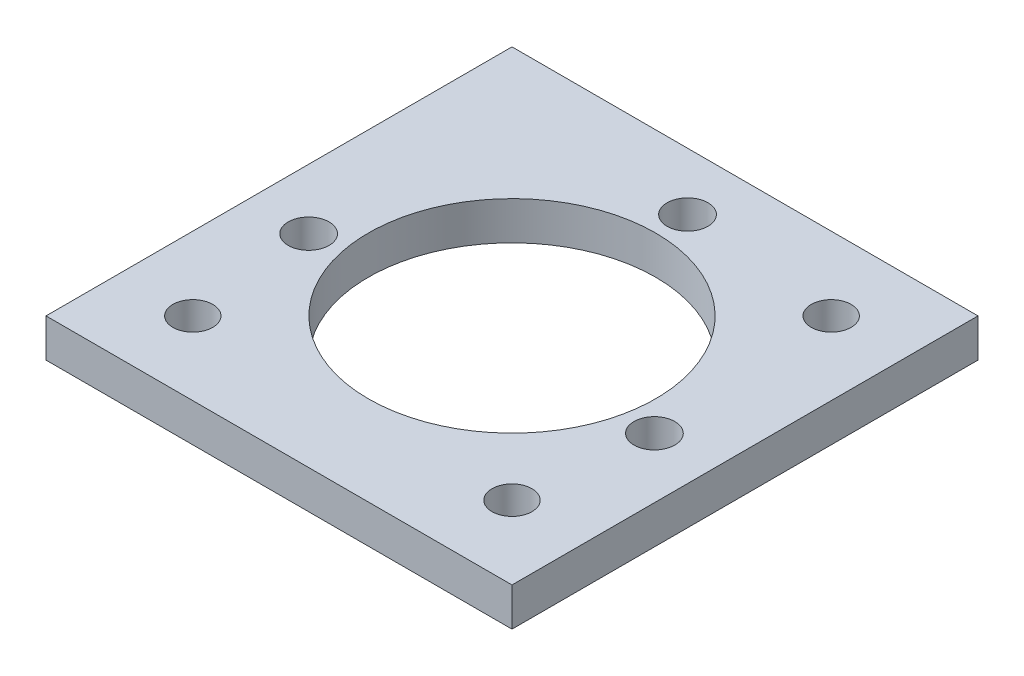
SolidWorks part; units mm, degrees
ref_plane "Front Plane" through (0, 0, 0) normal (0, 0, 1) x (1, 0, 0)
ref_plane "Top Plane" through (0, 0, 0) normal (0, 1, 0) x (1, 0, 0)
ref_plane "Right Plane" through (0, 0, 0) normal (1, 0, 0) x (0, 0, -1)
sketch "Sketch1" plane through (0, 0, 0) normal (0, 1, 0) x (1, 0, 0)
  line L0 (36.5, 64) -> (36.5, 36.5) construction
  line L1 (0, 0) -> (73, 0)
  line L2 (0, 0) -> (0, 73)
  line L3 (0, 73) -> (73, 73)
  line L4 (73, 0) -> (73, 73)
  line L5 (36.5, 36.5) -> (9.4178, 31.7247) construction
  line L6 (36.5, 36.5) -> (63.5822, 31.7247) construction
  line L7 (36.5, 36.5) -> (36.5, 0) construction
  line L8 (36.5, 36.5) -> (36.5, 73) construction
  line L9 (36.5, 36.5) -> (0, 36.5) construction
  line L10 (36.5, 36.5) -> (73, 36.5) construction
  circle A0 centre (36.5, 36.5) radius 27.5 construction
  circle A1 centre (36.5, 64) radius 3.2
  circle A4 centre (63.5822, 31.7247) radius 3.2
  circle A5 centre (9.4178, 31.7247) radius 3.2
  circle A6 centre (36.5, 36.5) radius 22.5
  point P16 (50, 50)
  dimension "D2" = 55
  dimension "D3" = 6.4
  dimension "D4" = 100
  dimension "D6" = 45
  dimension "D1" = 73
  dimension "D5" = 100
  dimension "D7" = 73
extrude "Boss-Extrude1" add sketch "Sketch1" along normal blind 6
hole_wizard "Tap Drill for M6 Helicoil1" positions "Sketch3" profile "Sketch5" hole size "M6x1.0" standard "DIN"
sketch "Sketch3" plane through (0, 0, 0) normal (0, -1, 0) x (-1, 0, 0)
  line L3 (-11.5, 11.5) -> (-61.5, 11.5)
  line L4 (-11.5, 11.5) -> (-11.5, 61.5)
  line L5 (-11.5, 61.5) -> (-61.5, 61.5)
  line L6 (-61.5, 11.5) -> (-61.5, 61.5)
  line L7 (-11.5, 11.5) -> (-61.5, 61.5) construction
  line L8 (-11.5, 61.5) -> (-61.5, 11.5) construction
  line L9 (-44.1084, 11.5) -> (-44.1084, 0) construction
  line L10 (0, 0) -> (-73, 0) construction
  line L12 (-49.7107, 61.5) -> (-49.7107, 73) construction
  line L13 (-73, 73) -> (0, 73) construction
  line L15 (-11.5, 49.3995) -> (0, 49.3995) construction
  line L16 (0, 73) -> (0, 0) construction
  line L18 (-61.5, 51.8894) -> (-73, 51.8894) construction
  line L19 (-73, 0) -> (-73, 73) construction
  point P14 (-11.5, 11.5)
  point P15 (-61.5, 11.5)
  point P74 (-61.5, 61.5)
  dimension "D1" = 50
  dimension "D2" = 50
sketch "Sketch5" plane through (11.5, 0, -11.5) normal (1, 0, 0) x (0, 0, -1)
  line L0 (0, 0) -> (0, 13.8177)
  line L1 (0, 13.8177) -> (3.125, 11.94)
  line L2 (3.125, 11.94) -> (3.125, 0)
  line L5 (3.125, 0) -> (0, 0)
  line L10 (0, 13.8177) -> (-3.125, 11.94) construction
  line L11 (0, -6.35) -> (0, 107.95) construction
  dimension "Hole Dia." = 6.25
  dimension "Hole Depth" = 11.94
  dimension "Drill Angle" = 118
